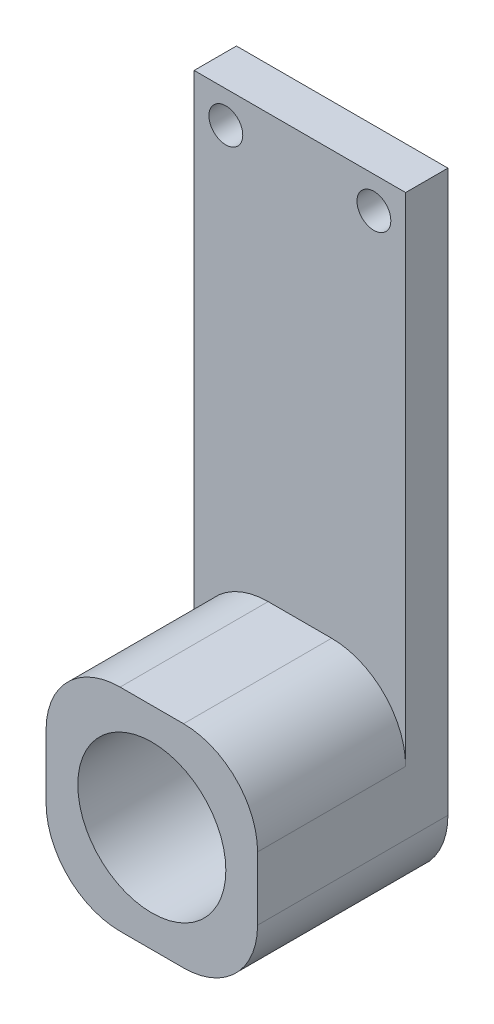
SolidWorks part; units mm, degrees
ref_plane "Front Plane" through (0, 0, 0) normal (0, 0, 1) x (1, 0, 0)
ref_plane "Top Plane" through (0, 0, 0) normal (0, 1, 0) x (1, 0, 0)
ref_plane "Right Plane" through (0, 0, 0) normal (1, 0, 0) x (0, 0, -1)
sketch "Sketch1" plane through (0, 0, 0) normal (0, 0, 1) x (1, 0, 0)
  line L1 (-17.8636, 21.6885) -> (-7.8636, 21.6885)
  line L2 (-17.8636, 21.6885) -> (-17.8636, -8.3115)
  line L3 (-17.8636, -8.3115) -> (-7.8636, -8.3115)
  line L4 (-7.8636, 21.6885) -> (-7.8636, -8.3115)
  dimension "D1" = 10
  dimension "D2" = 30
extrude "Boss-Extrude1" add sketch "Sketch1" along normal blind 2
sketch "Sketch2" plane through (0, 0, 2) normal (0, 0, 1) x (1, 0, 0)
  line L0 (-17.8636, 21.6885) -> (-17.8636, -8.3115) construction
  line L1 (-17.8636, 1.6885) -> (-7.8636, 1.6885)
  line L2 (-17.8636, 1.6885) -> (-17.8636, -8.3115)
  line L3 (-17.8636, -8.3115) -> (-7.8636, -8.3115)
  line L4 (-7.8636, 1.6885) -> (-7.8636, -8.3115)
  circle A0 centre (-12.8636, -3.3115) radius 3.5
  dimension "D1" = 7
  dimension "D2" = 5
  dimension "D3" = 5
extrude "Boss-Extrude2" add sketch "Sketch2" along normal blind 7
sketch "Sketch3" plane through (0, 0, 2) normal (0, 0, 1) x (1, 0, 0)
  line L0 (-7.8636, 21.6885) -> (-17.8636, 21.6885) construction
  line L1 (-7.8636, 1.6885) -> (-7.8636, 21.6885) construction
  line L2 (-17.8636, 21.6885) -> (-17.8636, 1.6885) construction
  circle A0 centre (-16.3636, 20.1885) radius 0.8
  circle A1 centre (-9.3636, 20.1885) radius 0.8
  dimension "D1" = 1.6
  dimension "D2" = 1.6
  dimension "D3" = 1.5
  dimension "D4" = 1.5
  dimension "D5" = 1.5
  dimension "D6" = 1.5
extrude "Cut-Extrude1" cut sketch "Sketch3" against normal blind 2
fillet "Fillet1" radius 3.5 4 edges at (-7.8636, -8.3115, 4.5) (-17.8636, -8.3115, 4.5)
sketch "Sketch4" plane through (0, 0, 2) normal (0, 0, 1) x (1, 0, 0)
  circle A0 centre (-12.8636, -3.3115) radius 1.5
  circle A1 centre (-12.8636, -3.3115) radius 3.5 construction
  dimension "D1" = 3
  dimension "D2" = 0
extrude "Cut-Extrude2" cut sketch "Sketch4" against normal blind 2
